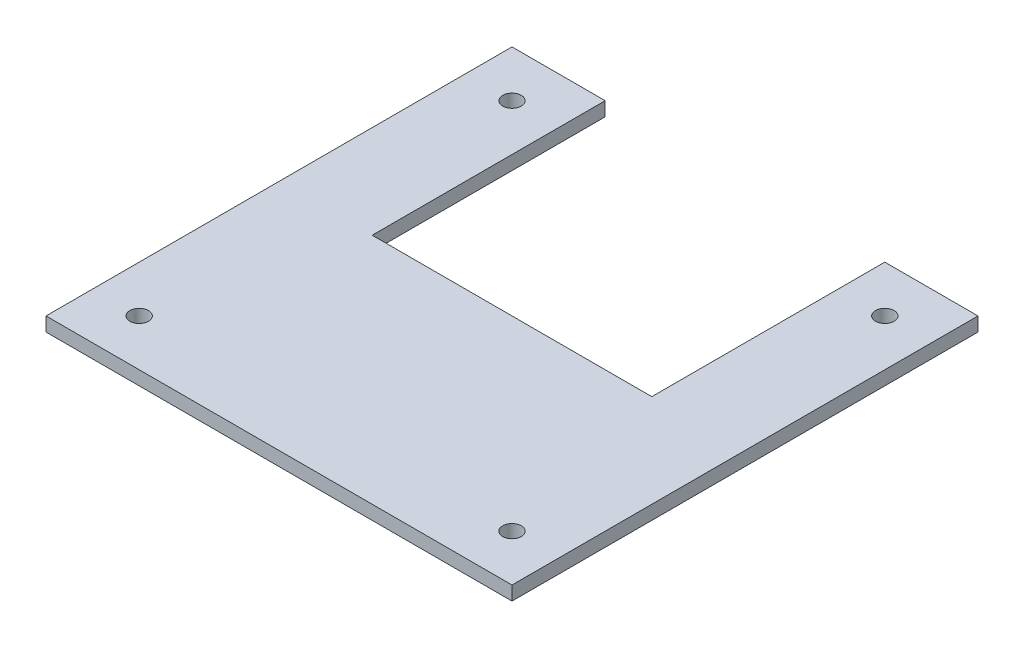
SolidWorks part; units mm, degrees
ref_plane "Front Plane" through (0, 0, 0) normal (0, 0, 1) x (1, 0, 0)
ref_plane "Top Plane" through (0, 0, 0) normal (0, 1, 0) x (1, 0, 0)
ref_plane "Right Plane" through (0, 0, 0) normal (1, 0, 0) x (0, 0, -1)
sketch "Sketch1" plane through (0, 0, 0) normal (0, 1, 0) x (1, 0, 0)
  line L0 (-30, 50) -> (-30, 0)
  line L1 (50, 50) -> (30, 50)
  line L2 (50, 50) -> (50, -50)
  line L3 (50, -50) -> (-50, -50)
  line L4 (-50, 50) -> (-50, -50)
  line L5 (50, 50) -> (-50, -50) construction
  line L6 (50, -50) -> (-50, 50) construction
  line L7 (-30, 0) -> (30, 0)
  line L8 (30, 0) -> (30, 50)
  line L9 (-30, 50) -> (-50, 50)
  line L10 (0, 0) -> (0, -50) construction
  circle A0 centre (-40, -40) radius 2
  circle A1 centre (40, -40) radius 2
  circle A2 centre (40, 40) radius 2
  circle A3 centre (-40, 40) radius 2
  point P0 (0, 0)
  dimension "D6" = 10
  dimension "D7" = 10
  dimension "D1" = 100
  dimension "D2" = 100
  dimension "D3" = 60
  dimension "D4" = 50
  dimension "D5" = 20
extrude "Boss-Extrude1" add sketch "Sketch1" along normal blind 3
